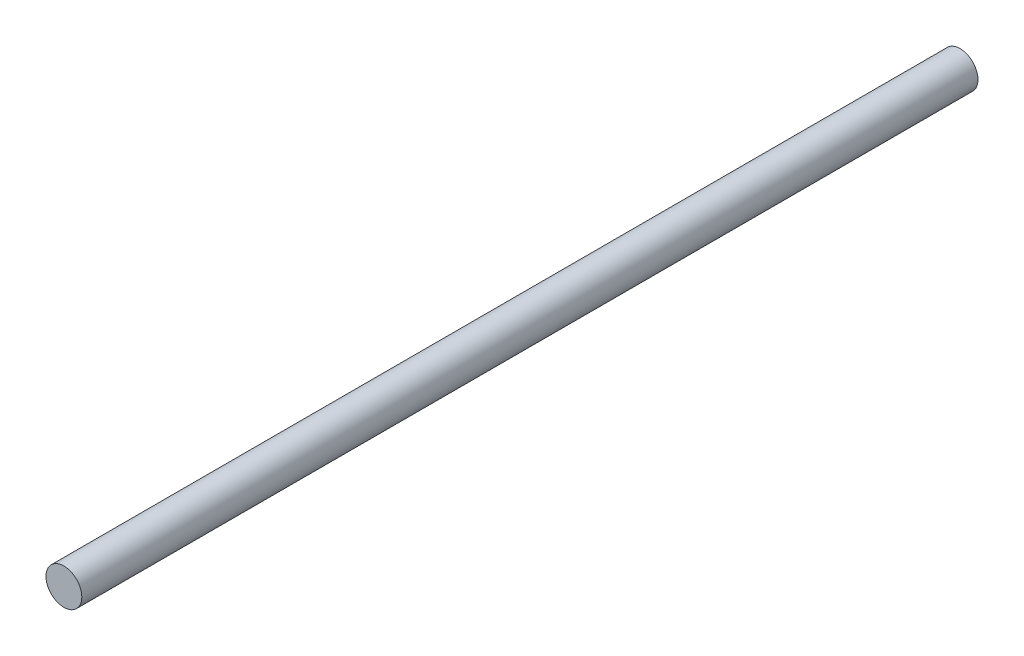
SolidWorks part; units mm, degrees
material "AISI 1020 Steel, Cold Rolled"
ref_plane "Płaszczyzna przednia" through (0, 0, 0) normal (0, 0, 1) x (1, 0, 0)
ref_plane "Płaszczyzna górna" through (0, 0, 0) normal (0, 1, 0) x (1, 0, 0)
ref_plane "Płaszczyzna prawa" through (0, 0, 0) normal (1, 0, 0) x (0, 0, -1)
sketch "Szkic1" plane through (0, 0, 0) normal (0, 0, 1) x (1, 0, 0)
  circle A0 centre (0, 0) radius 5
  dimension "D1" = 10
extrude "Dodanie-wyciągnięcie1" add sketch "Szkic1" along normal blind 250
